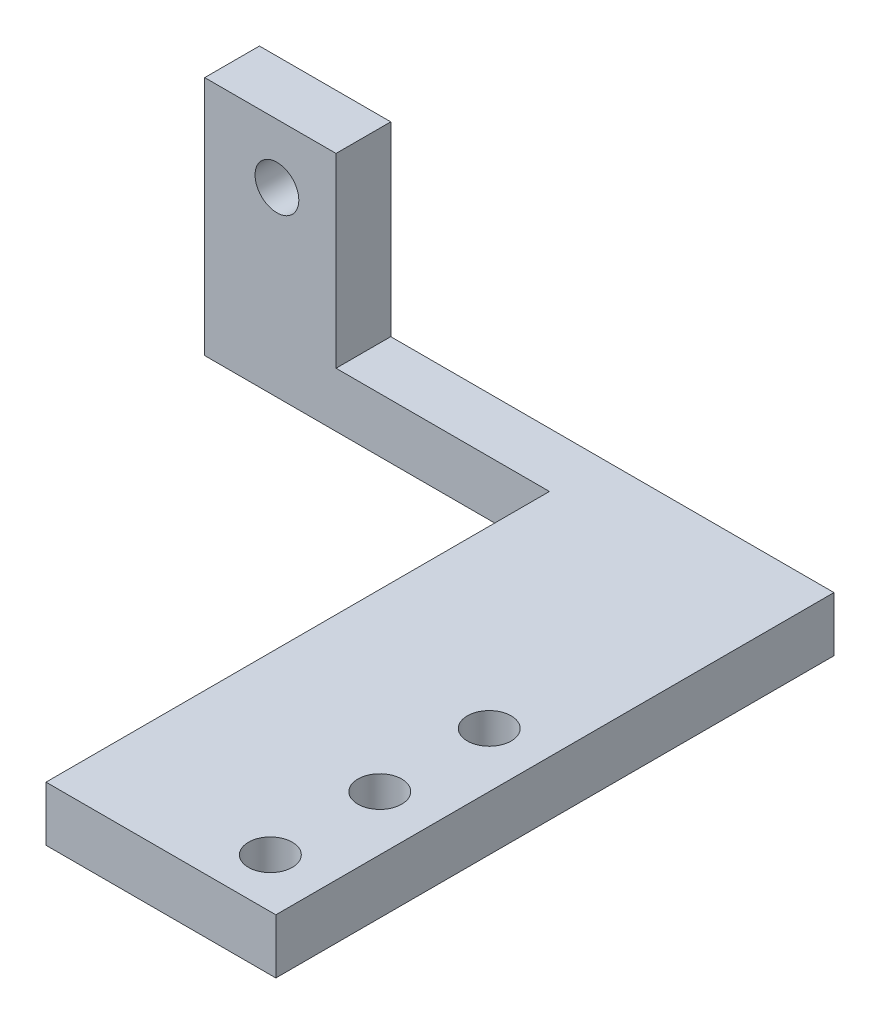
SolidWorks part; units mm, degrees
ref_plane "Alzado" through (0, 0, 0) normal (0, 0, 1) x (1, 0, 0)
ref_plane "Planta" through (0, 0, 0) normal (0, 1, 0) x (1, 0, 0)
ref_plane "Vista lateral" through (0, 0, 0) normal (1, 0, 0) x (0, 0, -1)
sketch "Croquis1" plane through (0, 0, 0) normal (0, 1, 0) x (1, 0, 0)
  line L1 (10.6967, 25.1492) -> (-5.3508, 25.1492)
  line L2 (10.6967, 25.1492) -> (10.6967, -25.8508)
  line L3 (10.6967, -25.8508) -> (-10.3033, -25.8508)
  line L4 (-10.3033, 20.1492) -> (-10.3033, -25.8508)
  line L7 (-5.3508, 25.1492) -> (-41.8033, 25.1492)
  line L9 (-10.3033, 20.1492) -> (-41.8033, 20.1492)
  line L10 (-41.8033, 25.1492) -> (-41.8033, 20.1492)
  point P0 (0, 0)
  dimension "D1" = 51
  dimension "D2" = 5
  dimension "D3" = 52.5
  dimension "D4" = 21
extrude "Saliente-Extruir1" add sketch "Croquis1" along normal blind 5
sketch "Croquis2" plane through (0, 5, 0) normal (0, 1, 0) x (1, 0, 0)
  line L0 (-41.8033, 25.1492) -> (-41.8033, 20.1492)
  line L1 (-41.8033, 25.1492) -> (-29.8033, 25.1492)
  line L2 (-41.8033, 20.1492) -> (-29.8033, 20.1492)
  line L3 (-29.8033, 25.1492) -> (-29.8033, 20.1492)
  dimension "D1" = 12
extrude "Saliente-Extruir2" add sketch "Croquis2" along normal blind 17
sketch "Croquis3" plane through (0, 0, 0) normal (0, -1, 0) x (1, 0, 0)
  line L0 (7.6967, 31.0739) -> (7.6967, -32.2381) construction
  line L1 (-14.9403, 21.3508) -> (17.8587, 21.3508) construction
  line L2 (-14.9403, 11.3508) -> (18.5966, 11.3508) construction
  line L3 (-16.7398, 1.3508) -> (22.0966, 1.3508) construction
  line L4 (-10.3768, 23.3508) -> (16.4579, 23.3508) construction
  line L5 (-10.3033, 25.8508) -> (10.6967, 25.8508) construction
  line L6 (10.6967, 25.8508) -> (10.6967, -25.1492) construction
  circle A1 centre (5.6967, 21.3508) radius 2
  circle A2 centre (5.6967, 11.3508) radius 2
  circle A3 centre (5.6967, 1.3508) radius 2
  dimension "D4" = 3
  dimension "D1" = 10
  dimension "D2" = 10
  dimension "D3" = 2.5
extrude "Cortar-Extruir1" cut sketch "Croquis3" against normal blind 20
sketch "Croquis4" plane through (0, 0, -20.1492) normal (0, 0, 1) x (1, 0, 0)
  line L0 (-45.3916, 18.6) -> (-24.31, 18.6) construction
  line L1 (-33.2033, 27.6123) -> (-33.2033, 1.5282) construction
  line L2 (-29.8033, 22) -> (-29.8033, 5) construction
  line L3 (-41.8033, 22) -> (-29.8033, 22) construction
  circle A0 centre (-35.2033, 16.6) radius 2
  dimension "D1" = 3.4
  dimension "D2" = 3.4
extrude "Cortar-Extruir2" cut sketch "Croquis4" against normal blind 20
